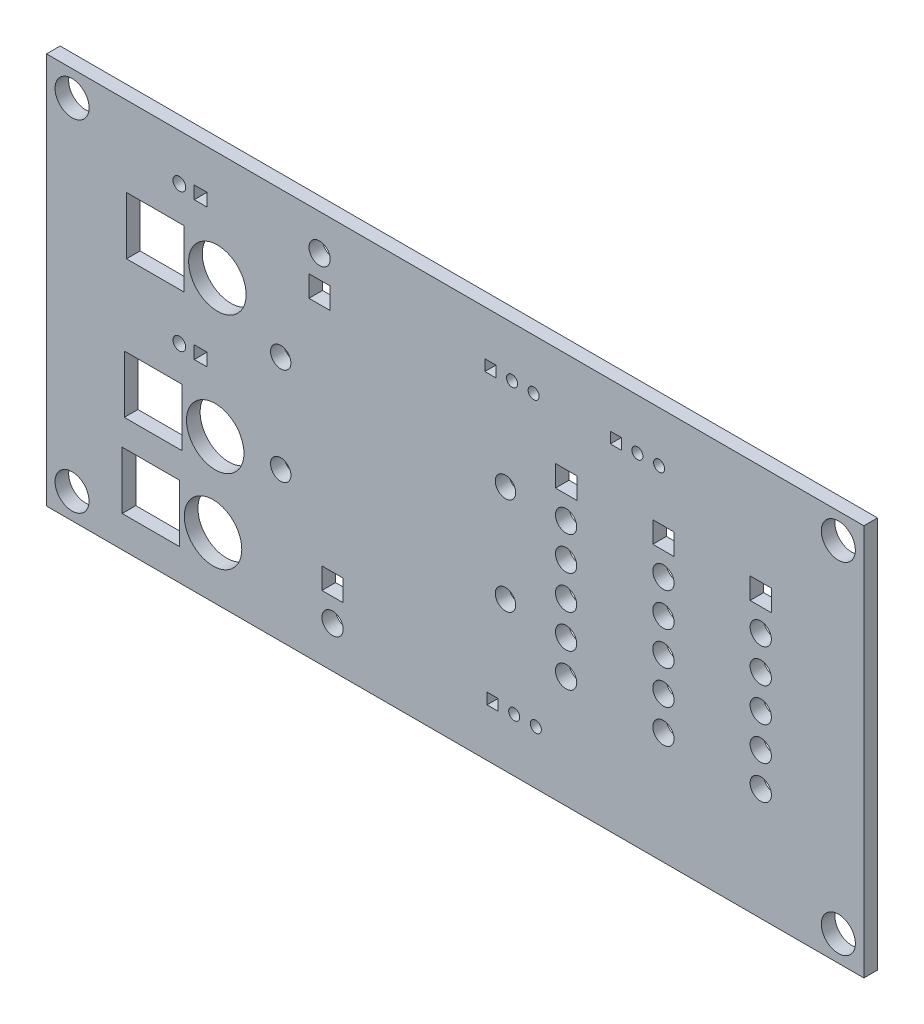
SolidWorks part; units mm, degrees
ref_plane "Plan de face" through (0, 0, 0) normal (0, 0, 1) x (1, 0, 0)
ref_plane "Plan de dessus" through (0, 0, 0) normal (0, 1, 0) x (1, 0, 0)
ref_plane "Plan de droite" through (0, 0, 0) normal (1, 0, 0) x (0, 0, -1)
sketch "Model" plane through (0, 0, 0) normal (0, 0, 1) x (1, 0, 0)
  line L0 (-57.678, 33.548) -> (-60.178, 33.548)
  line L1 (-60.178, 33.548) -> (-60.178, 36.048)
  line L2 (-60.178, 36.048) -> (-57.678, 36.048)
  line L3 (-57.678, 36.048) -> (-57.678, 33.548)
  line L4 (-58.654, 7.092) -> (-56.154, 7.092)
  line L5 (-56.154, 7.092) -> (-56.154, 4.592)
  line L6 (-56.154, 4.592) -> (-58.654, 4.592)
  line L7 (-58.654, 4.592) -> (-58.654, 7.092)
  line L8 (-8.362, 31.222) -> (-5.862, 31.222)
  line L9 (-5.862, 31.222) -> (-5.862, 28.722)
  line L10 (-5.862, 28.722) -> (-8.362, 28.722)
  line L11 (-8.362, 28.722) -> (-8.362, 31.222)
  line L12 (-19.792, 31.222) -> (-17.292, 31.222)
  line L13 (-17.292, 31.222) -> (-17.292, 28.722)
  line L14 (-17.292, 28.722) -> (-19.792, 28.722)
  line L15 (-19.792, 28.722) -> (-19.792, 31.222)
  line L16 (-31.222, 31.222) -> (-28.722, 31.222)
  line L17 (-28.722, 31.222) -> (-28.722, 28.722)
  line L18 (-28.722, 28.722) -> (-31.222, 28.722)
  line L19 (-31.222, 28.722) -> (-31.222, 31.222)
  line L36 (-39.258, 2.652) -> (-39.258, 3.952)
  line L37 (-39.258, 3.952) -> (-37.958, 3.952)
  line L38 (-37.958, 3.952) -> (-37.958, 2.652)
  line L39 (-37.958, 2.652) -> (-39.258, 2.652)
  line L40 (-24.78, 36.434) -> (-24.78, 37.734)
  line L41 (-24.78, 37.734) -> (-23.48, 37.734)
  line L42 (-23.48, 37.734) -> (-23.48, 36.434)
  line L43 (-23.48, 36.434) -> (-24.78, 36.434)
  line L44 (-39.512, 36.434) -> (-39.512, 37.734)
  line L45 (-39.512, 37.734) -> (-38.212, 37.734)
  line L46 (-38.212, 37.734) -> (-38.212, 36.434)
  line L47 (-38.212, 36.434) -> (-39.512, 36.434)
  line L48 (-72.148, 22.086) -> (-72.148, 20.586)
  line L49 (-72.148, 20.586) -> (-73.648, 20.586)
  line L50 (-73.648, 20.586) -> (-73.648, 22.086)
  line L51 (-73.648, 22.086) -> (-72.148, 22.086)
  line L52 (-72.148, 38.342) -> (-72.148, 36.842)
  line L53 (-72.148, 36.842) -> (-73.648, 36.842)
  line L54 (-73.648, 36.842) -> (-73.648, 38.342)
  line L55 (-73.648, 38.342) -> (-72.148, 38.342)
  line L56 (-82.115, 0.689) -> (-82.115, 7.439)
  line L57 (-82.115, 7.439) -> (-75.365, 7.439)
  line L58 (-75.365, 7.439) -> (-75.365, 0.689)
  line L59 (-75.365, 0.689) -> (-82.115, 0.689)
  line L60 (-81.861, 10.595) -> (-81.861, 17.345)
  line L61 (-81.861, 17.345) -> (-75.111, 17.345)
  line L62 (-75.111, 17.345) -> (-75.111, 10.595)
  line L63 (-75.111, 10.595) -> (-81.861, 10.595)
  line L64 (-81.607, 26.851) -> (-81.607, 33.601)
  line L65 (-81.607, 33.601) -> (-74.857, 33.601)
  line L66 (-74.857, 33.601) -> (-74.857, 26.851)
  line L67 (-74.857, 26.851) -> (-81.607, 26.851)
  line L148 (-91, -3) -> (-91, 43)
  line L149 (-91, 43) -> (5, 43)
  line L150 (5, 43) -> (5, -3)
  line L151 (5, -3) -> (-91, -3)
  circle A0 centre (-58.928, 38.758) radius 1.25
  circle A1 centre (-57.404, 1.882) radius 1.25
  circle A2 centre (-88, 40) radius 2
  circle A3 centre (-88, 0) radius 2
  circle A4 centre (2, 0) radius 2
  circle A5 centre (2, 40) radius 2
  circle A6 centre (-7.112, 26.012) radius 1.25
  circle A7 centre (-7.112, 22.052) radius 1.25
  circle A8 centre (-7.112, 18.092) radius 1.25
  circle A9 centre (-7.112, 14.132) radius 1.25
  circle A10 centre (-7.112, 10.172) radius 1.25
  circle A11 centre (-18.542, 26.012) radius 1.25
  circle A12 centre (-18.542, 22.052) radius 1.25
  circle A13 centre (-18.542, 18.092) radius 1.25
  circle A14 centre (-18.542, 14.132) radius 1.25
  circle A15 centre (-18.542, 10.172) radius 1.25
  circle A16 centre (-29.972, 26.012) radius 1.25
  circle A17 centre (-29.972, 22.052) radius 1.25
  circle A18 centre (-29.972, 18.092) radius 1.25
  circle A19 centre (-29.972, 14.132) radius 1.25
  circle A20 centre (-29.972, 10.172) radius 1.25
  circle A25 centre (-36.068, 3.302) radius 0.65
  circle A26 centre (-33.528, 3.302) radius 0.65
  circle A27 centre (-21.59, 37.084) radius 0.65
  circle A28 centre (-19.05, 37.084) radius 0.65
  circle A29 centre (-36.322, 37.084) radius 0.65
  circle A30 centre (-33.782, 37.084) radius 0.65
  circle A31 centre (-63.492, 14.478) radius 1.2
  circle A32 centre (-37.092, 14.478) radius 1.2
  circle A33 centre (-63.492, 25.908) radius 1.2
  circle A34 centre (-37.092, 25.908) radius 1.2
  circle A35 centre (-75.398, 21.336) radius 0.75
  circle A36 centre (-75.398, 37.592) radius 0.75
  circle A37 centre (-71.44, 4.064) radius 3.375
  circle A38 centre (-71.186, 13.97) radius 3.375
  circle A39 centre (-70.932, 30.226) radius 3.375
extrude "Boss.-Extru.1" add sketch "Model" along normal blind 1.6
